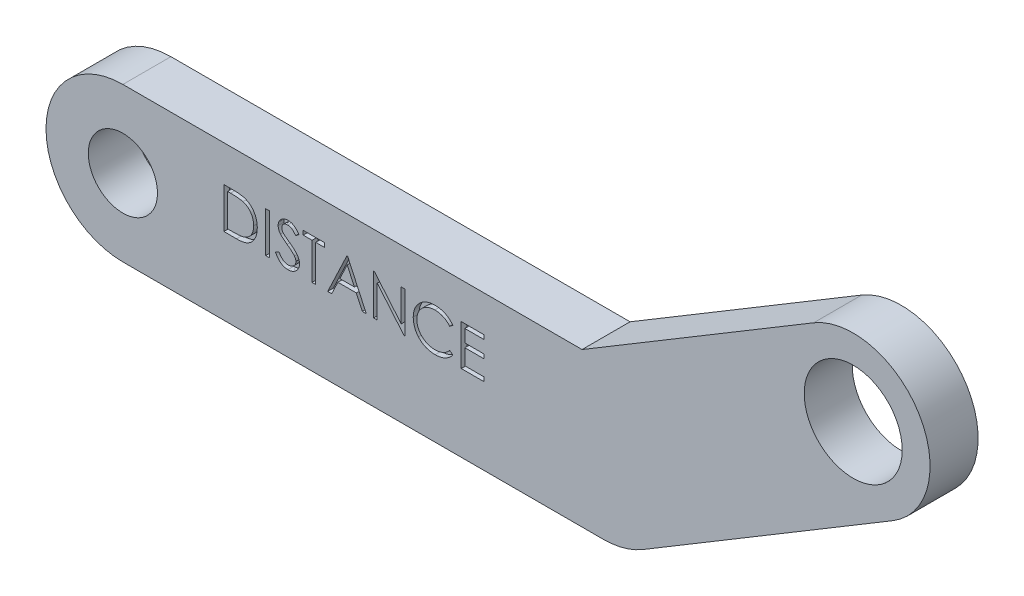
SolidWorks part; units mm, degrees
ref_plane "Front Plane" through (0, 0, 0) normal (0, 0, 1) x (1, 0, 0)
ref_plane "Top Plane" through (0, 0, 0) normal (0, 1, 0) x (1, 0, 0)
ref_plane "Right Plane" through (0, 0, 0) normal (1, 0, 0) x (0, 0, -1)
sketch "Sketch1" plane through (0, 0, 0) normal (0, 0, 1) x (1, 0, 0)
  line L0 (0, 0) -> (0, -7.8) construction
  line L1 (0, -7.8) -> (-38, -7.8) construction
  line L2 (-38, -7.8) -> (-13, -7.8) construction
  line L3 (-38, -3.8) -> (-13, -3.8)
  line L4 (-38, -11.8) -> (-13, -11.8)
  line L5 (-13, -7.8) -> (0, 0) construction
  line L6 (-15.058, -4.37) -> (-2.058, 3.43)
  line L7 (-10.942, -11.23) -> (2.058, -3.43)
  circle A0 centre (0, 0) radius 2.55
  circle A1 centre (-38, -7.8) radius 1.8
  arc A2 (-38, -3.8) -> (-38, -11.8) centre (-38, -7.8) ccw
  arc A3 (-13, -11.8) -> (-13, -3.8) centre (-13, -7.8) ccw
  arc A4 (-15.058, -4.37) -> (-10.942, -11.23) centre (-13, -7.8) ccw
  arc A5 (2.058, -3.43) -> (-2.058, 3.43) centre (0, 0) ccw
  point P7 (-25.5, -7.8)
  point P13 (-6.5, -3.9)
  dimension "D1" = 5.1
  dimension "D2" = 3.6
  dimension "D5" = 4
  dimension "D6" = 4
  dimension "Vertical" = 7.8
  dimension "Horizontal" = 38
  dimension "D7" = 25
extrude "Boss-Extrude1" add sketch "Sketch1" along normal mid plane 2.5 contours A4 L6 L3 A2 L4 A1 | L6 A4 A3 L3 | L7 A5 L6 L3 A3 A0
sketch "Sketch2" plane through (0, 0, 1.25) normal (0, 0, 1) x (1, 0, 0)
  line L0 (-38, -7.8) -> (-14.1079, -7.8) construction
  text T0 "DISTANCE" font "Century Gothic" height in points 8
extrude "Cut-Extrude1" cut sketch "Sketch2" against normal blind 0.3
mirror "Mirror1" about plane through (0, 0, 0) normal (0, 0, 1) of "Cut-Extrude1"
equation "\"DistanceScale\"= 1"
equation "\"Horizontal@Sketch1\"= \"DistanceScale\" * 38"
equation "\"Vertical@Sketch1\"= \"DistanceScale\" * 7.8"
